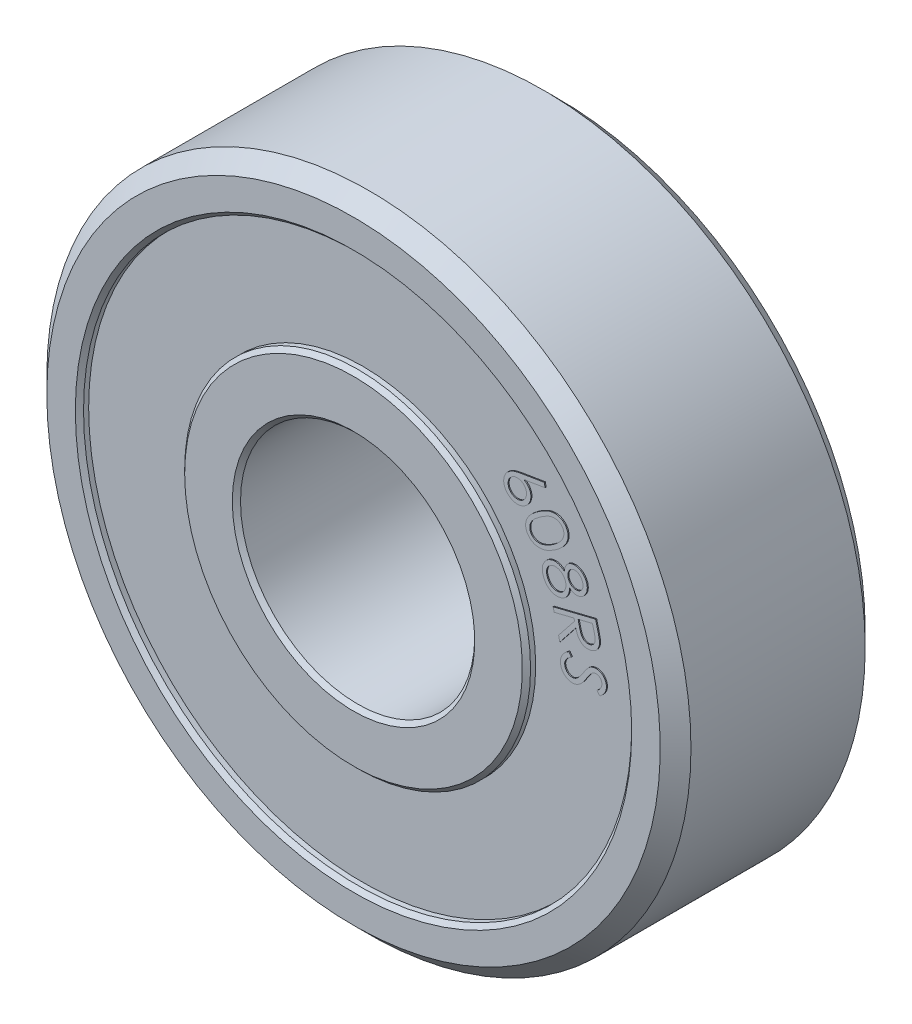
SolidWorks part; units mm, degrees
ref_plane "Front Plane" through (0, 0, 0) normal (0, 0, 1) x (1, 0, 0)
ref_plane "Top Plane" through (0, 0, 0) normal (0, 1, 0) x (1, 0, 0)
ref_plane "Right Plane" through (0, 0, 0) normal (1, 0, 0) x (0, 0, -1)
sketch "Sketch3" plane through (0, 0, 0) normal (0, 1, 0) x (1, 0, 0)
  line L0 (0, 0) -> (-11, 0) construction
  line L1 (0, 0) -> (0, 3.5) construction
  line L2 (0, 3.5) -> (-11, 3.5) construction
  line L3 (-11, 3.5) -> (-11, 0) construction
  line L4 (-4, 3.5) -> (-4, -3.5)
  line L5 (-4, 3.5) -> (-5.907, 3.5)
  line L6 (-11, -3.5) -> (-11, 3.5)
  line L7 (-11, 3.5) -> (-9.361, 3.5)
  line L8 (-9.361, 3.5) -> (-9.361, 3.185)
  line L9 (-9.361, 3.185) -> (-5.907, 3.185)
  line L10 (-5.907, 3.185) -> (-5.907, 3.5)
  line L11 (-4, -3.5) -> (-5.907, -3.5)
  line L12 (-5.907, -3.185) -> (-5.907, -3.5)
  line L13 (-9.361, -3.185) -> (-5.907, -3.185)
  line L14 (-9.361, -3.5) -> (-9.361, -3.185)
  line L15 (-11, -3.5) -> (-9.361, -3.5)
  point P12 (-4, 0)
  dimension "D1" = 11
  dimension "D2" = 3.5
  dimension "D3" = 4
  dimension "D4" = 5.907
  dimension "D5" = 9.361
  dimension "D6" = 0.315
revolve "Revolve1" add sketch "Sketch3" angle 360 about L1
chamfer "Chamfer1" distance 0.525 angle 45 2 edges at (11, 0, -3.5) (11, 0, 3.5)
chamfer "Chamfer2" distance 0.14 angle 45 6 edges at (5.907, 0, 3.5) (4, 0, 3.5) (4, 0, -3.5) (5.907, 0, -3.5) (9.361, 0, 3.5) (9.361, 0, -3.5)
sketch "Sketch4" plane through (0, 0, 3.185) normal (0, 0, 1) x (1, 0, 0)
  circle A0 centre (0, 0) radius 6.875 construction
  text T0 "608RS" font "Century Gothic" height 1.5
  dimension "D1" = 13.75
extrude "Boss-Extrude1" add sketch "Sketch4" along normal blind 0.035
sketch "Sketch5" plane through (0, 0, -3.185) normal (0, 0, -1) x (-1, 0, 0)
  circle A0 centre (0, 0) radius 6.875 construction
  text T0 "608RS" font "Century Gothic" height 1.5
  dimension "D1" = 13.75
extrude "Boss-Extrude2" add sketch "Sketch5" along normal blind 0.035
equation "\"InnerDiameter\"= 8mm"
equation "\"OuterDiameter\"= 22mm"
equation "\"Width\"= 7mm"
equation "\"D1@Sketch3\"= 0.5 * \"OuterDiameter\""
equation "\"D2@Sketch3\"= 0.5 * \"Width\""
equation "\"D3@Sketch3\"=0.5 * \"InnerDiameter\""
equation "\"D4@Sketch3\"= (\"OuterDiameter\" * 0.537 )/2"
equation "\"D5@Sketch3\"= (\"OuterDiameter\" *  0.851)/2"
equation "\"D6@Sketch3\"=\"Width\" * 0.045"
equation "\"D1@Chamfer1\"=\"Width\" * 0.075"
equation "\"D1@Chamfer2\"=\"Width\"*0.02"
equation "\"D1@Sketch4\"=\"OuterDiameter\"*0.625"
equation "\"D1@Boss-Extrude1\"=\"Width\"* 0.005"
equation "\"D1@Sketch5\"=\"OuterDiameter\" *0.625"
equation "\"D1@Boss-Extrude2\"=\"Width\"*0.005"
